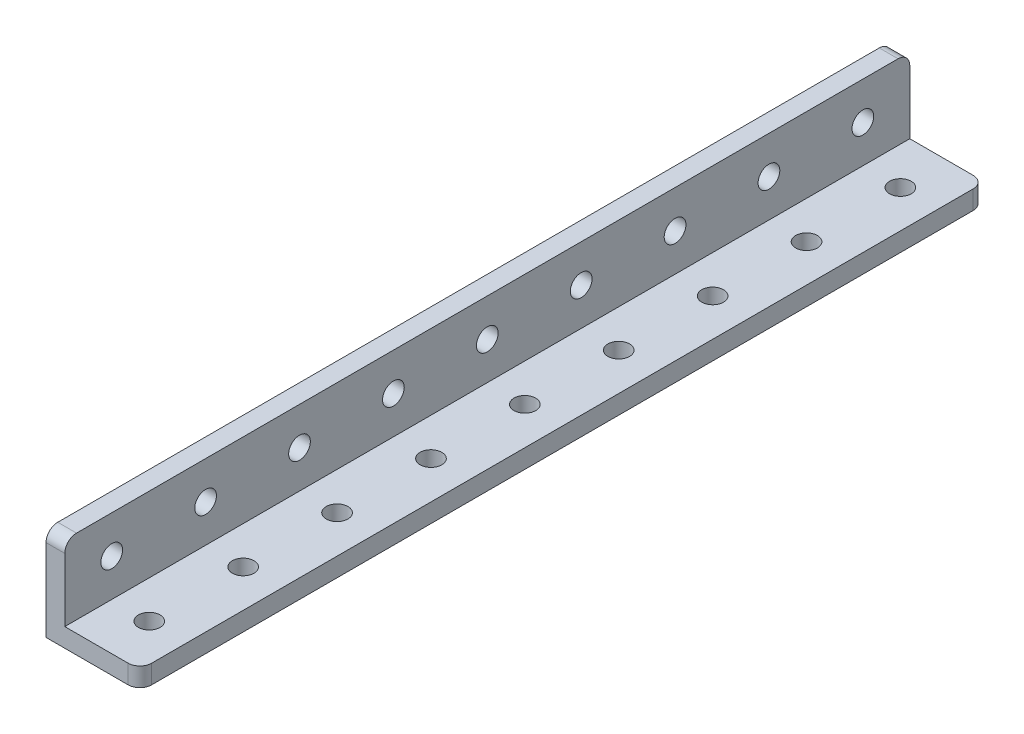
SolidWorks part; units mm, degrees
ref_plane "Front Plane" through (0, 0, 0) normal (0, 0, 1) x (1, 0, 0)
ref_plane "Top Plane" through (0, 0, 0) normal (0, 1, 0) x (1, 0, 0)
ref_plane "Right Plane" through (0, 0, 0) normal (1, 0, 0) x (0, 0, -1)
sketch "Sketch1" plane through (0, 0, 0) normal (0, 0, 1) x (1, 0, 0)
  line L0 (0, 16) -> (0, 0)
  line L1 (0, 0) -> (16, 0)
  line L2 (16, 0) -> (16, 3.2)
  line L3 (16, 3.2) -> (3.2, 3.2)
  line L4 (3.2, 3.2) -> (3.2, 16)
  line L5 (3.2, 16) -> (0, 16)
  dimension "D1" = 16
  dimension "D2" = 16
  dimension "D3" = 3.2
  dimension "D4" = 3.2
extrude "Boss-Extrude1" add sketch "Sketch1" against normal blind 144
sketch "Sketch2" plane through (0, 0, 0) normal (-1, 0, 0) x (0, 0, 1)
  line L0 (-154.1379, 9.6) -> (18.0301, 9.6) construction
  line L1 (-144, 0) -> (0, 0) construction
  line L2 (-72, 21.373) -> (-72, -6.9807) construction
  circle B0 centre (-88, 9.6) radius 1.85
  circle B1 centre (-104, 9.6) radius 1.85
  circle B2 centre (-120, 9.6) radius 1.85
  circle B3 centre (-136, 9.6) radius 1.85
  circle B4 centre (-8, 9.6) radius 1.85
  circle B5 centre (-24, 9.6) radius 1.85
  circle B6 centre (-40, 9.6) radius 1.85
  circle B7 centre (-56, 9.6) radius 1.85
  circle B8 centre (-72, 9.6) radius 1.85
  dimension "D1" = 9.6
sketch_block_instance "Block1-1"
sketch_block "Block1"
extrude "Cut-Extrude1" cut sketch "Sketch2" against normal through all
sketch "Sketch3" plane through (0, 0, 0) normal (0, -1, 0) x (1, 0, 0)
  line L0 (9.6, 8.7023) -> (9.6, -150.3269) construction
  line L1 (0, -144) -> (0, 0) construction
  line L2 (-8.3353, -72) -> (37.7693, -72) construction
  circle B0 centre (9.6, -88) radius 1.85
  circle B1 centre (9.6, -104) radius 1.85
  circle B2 centre (9.6, -120) radius 1.85
  circle B3 centre (9.6, -136) radius 1.85
  circle B4 centre (9.6, -8) radius 1.85
  circle B5 centre (9.6, -24) radius 1.85
  circle B6 centre (9.6, -40) radius 1.85
  circle B7 centre (9.6, -56) radius 1.85
  circle B8 centre (9.6, -72) radius 1.85
  dimension "D1" = 9.6
sketch_block_instance "Block1-2"
extrude "Cut-Extrude2" cut sketch "Sketch3" against normal through all
fillet "Fillet1" radius 2 4 edges at (1.6, 16, -144) (16, 1.6, -144) (16, 1.6, 0) (1.6, 16, 0)
